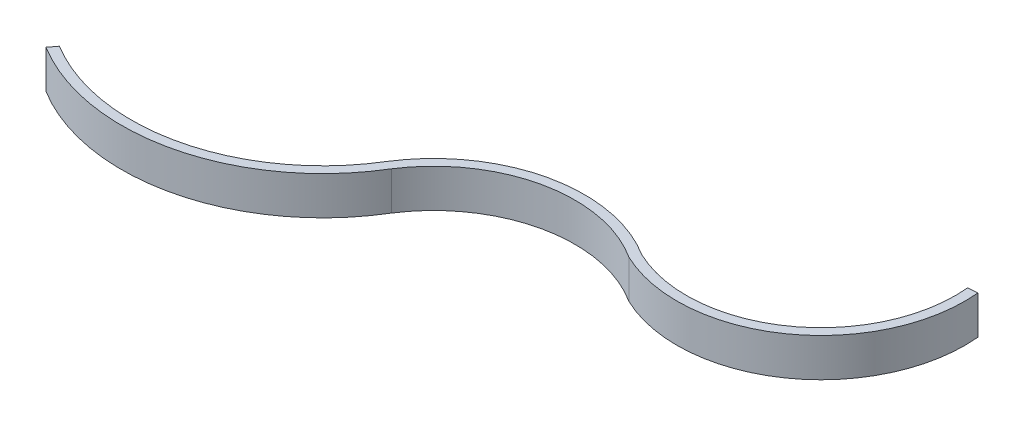
SolidWorks part; units mm, degrees
ref_plane "Front Plane" through (0, 0, 0) normal (0, 0, 1) x (1, 0, 0)
ref_plane "Top Plane" through (0, 0, 0) normal (0, 1, 0) x (1, 0, 0)
ref_plane "Right Plane" through (0, 0, 0) normal (1, 0, 0) x (0, 0, -1)
sketch "Sketch2" plane through (0, 0, 0) normal (0, 1, 0) x (1, 0, 0)
  line L0 (-3459.4391, -1276.3364) -> (-3489.7078, -1316.1334)
  line L1 (49.7785, 4.7016) -> (0, 0)
  arc A0 (-1000, -699.2902) -> (0, 0) centre (-698.3769, -65.9619) ccw
  arc A1 (-1000, -699.2902) -> (-2085.1056, -942.8584) centre (-1420.7687, -1363.6271) ccw
  arc A2 (-2085.1056, -942.8584) -> (-3459.4391, -1276.3364) centre (-2939.0113, -422.4307) cw
  arc A3 (49.7785, 4.7016) -> (-1021.4989, -744.4322) centre (-698.3769, -65.9619) cw
  arc A4 (-1021.4989, -744.4322) -> (-2039.9636, -964.3573) centre (-1420.7687, -1363.6271) ccw
  arc A5 (-2039.9636, -964.3573) -> (-3489.7078, -1316.1334) centre (-2939.0113, -422.4307) cw
  dimension "D1" = 1000
  dimension "D2" = 786.3777
  dimension "D3" = 701.4851
  dimension "D6" = 243.5682
  dimension "D11" = 0
  dimension "D12" = 50
  dimension "D14" = 0
  dimension "D16" = 0
  dimension "D17" = 49.6153
  dimension "D19" = 49.7482
  dimension "D4" = 1000
  dimension "D5" = 699.2902
  dimension "D7" = 1085.1056
  dimension "D8" = 1374.3335
  dimension "D9" = 333.478
  dimension "D10" = 50
  dimension "D13" = 50
  dimension "D15" = 50
  dimension "D18" = 50
extrude "Boss-Extrude1" add sketch "Sketch2" along normal blind 200
